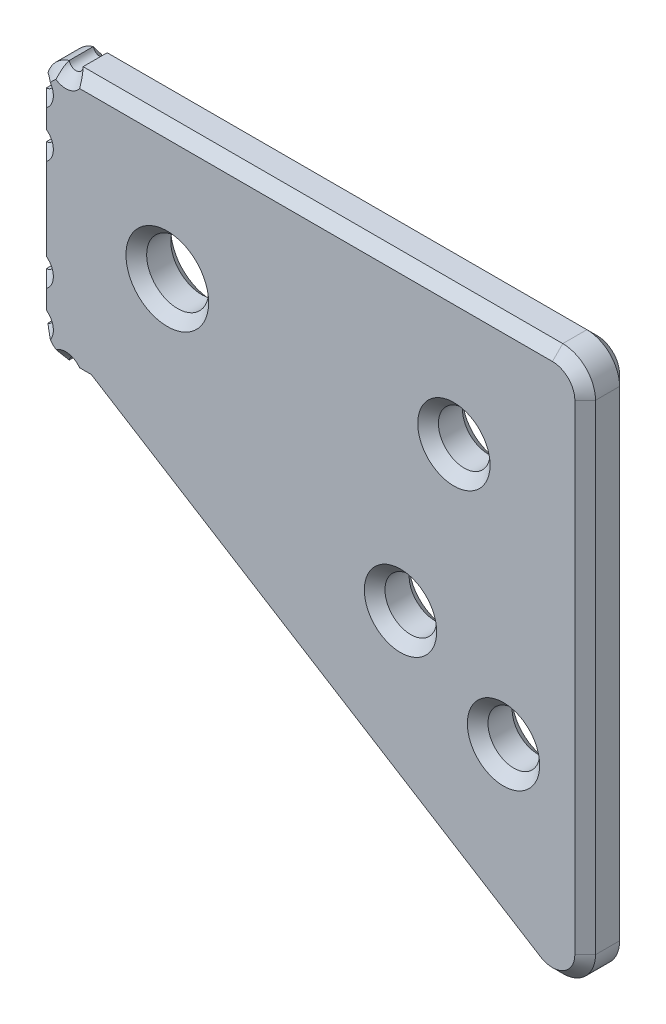
SolidWorks part; units mm, degrees
ref_plane "Front Plane" through (0, 0, 0) normal (0, 0, 1) x (1, 0, 0)
ref_plane "Top Plane" through (0, 0, 0) normal (0, 1, 0) x (1, 0, 0)
ref_plane "Right Plane" through (0, 0, 0) normal (1, 0, 0) x (0, 0, -1)
sketch "Sketch1" plane through (0, 0, 0) normal (0, 0, 1) x (1, 0, 0)
  line L3 (435.95, -297.537) -> (-11.4581, -19.05) construction
  line L9 (53.3811, -59.4088) -> (-11.4581, -19.05)
  line L11 (19.05, 19.05) -> (-13.7235, 19.05)
  line L12 (-19.05, -5.7912) -> (-19.05, 5.7912)
  line L13 (60.6412, -19.05) -> (60.6412, 14.3)
  line L14 (60.6412, -19.05) -> (60.6412, -55.3762)
  line L24 (19.05, 19.05) -> (19.05, 17.3228)
  line L25 (19.05, 17.3228) -> (704.05, 17.3228)
  line L26 (704.05, 17.3228) -> (704.05, 19.05)
  line L27 (704.05, 19.05) -> (19.05, 19.05)
  line L31 (55.8912, 19.05) -> (19.05, 19.05)
  line L44 (19.05, -6.9643) -> (19.05, -5.7912)
  line L45 (17.3228, -4.064) -> (16.7132, -4.064)
  line L46 (14.986, -5.7912) -> (14.986, -8.9963)
  line L47 (12.7826, -9.909) -> (7.8889, -5.0152)
  line L48 (6.985, -2.833) -> (6.985, 2.833)
  line L49 (7.8889, 5.0152) -> (12.7826, 9.909)
  line L50 (14.986, 8.9963) -> (14.986, 5.7912)
  line L51 (16.7132, 4.064) -> (17.3228, 4.064)
  line L52 (19.05, 5.7912) -> (19.05, 6.9643)
  line L53 (19.05, 8.9963) -> (19.05, 13.7235)
  line L54 (13.7235, 19.05) -> (8.9963, 19.05)
  line L55 (6.9643, 19.05) -> (5.7912, 19.05)
  line L56 (4.064, 17.3228) -> (4.064, 16.7132)
  line L57 (5.7912, 14.986) -> (8.9963, 14.986)
  line L58 (9.909, 12.7826) -> (5.0152, 7.8889)
  line L59 (2.833, 6.985) -> (-2.833, 6.985)
  line L60 (-5.0152, 7.8889) -> (-9.909, 12.7826)
  line L61 (-8.9963, 14.986) -> (-5.7912, 14.986)
  line L62 (-4.064, 16.7132) -> (-4.064, 17.3228)
  line L63 (-5.7912, 19.05) -> (-6.9643, 19.05)
  line L64 (-8.9963, 19.05) -> (-13.7235, 19.05)
  line L65 (-19.05, 13.7235) -> (-19.05, 8.9963)
  line L66 (-19.05, 6.9643) -> (-19.05, 5.7912)
  line L67 (-17.3228, 4.064) -> (-16.7132, 4.064)
  line L68 (-14.986, 5.7912) -> (-14.986, 8.9963)
  line L69 (-12.7826, 9.909) -> (-7.8889, 5.0152)
  line L70 (-6.985, 2.833) -> (-6.985, -2.833)
  line L71 (-7.8889, -5.0152) -> (-12.7826, -9.909)
  line L72 (-14.986, -8.9963) -> (-14.986, -5.7912)
  line L73 (-16.7132, -4.064) -> (-17.3228, -4.064)
  line L74 (-19.05, -5.7912) -> (-19.05, -6.9643)
  line L75 (-19.05, -8.9963) -> (-19.05, -13.7235)
  line L76 (-13.7235, -19.05) -> (-8.9963, -19.05)
  line L77 (-6.9643, -19.05) -> (-5.7912, -19.05)
  line L78 (-4.064, -17.3228) -> (-4.064, -16.7132)
  line L79 (-5.7912, -14.986) -> (-8.9963, -14.986)
  line L80 (-9.909, -12.7826) -> (-5.0152, -7.8889)
  line L81 (-2.833, -6.985) -> (2.833, -6.985)
  line L82 (5.0152, -7.8889) -> (9.909, -12.7826)
  line L83 (8.9963, -14.986) -> (5.7912, -14.986)
  line L84 (4.064, -16.7132) -> (4.064, -17.3228)
  line L85 (5.7912, -19.05) -> (6.9643, -19.05)
  line L86 (8.9963, -19.05) -> (13.7235, -19.05)
  line L87 (19.05, -13.7235) -> (19.05, -8.9963)
  line L108 (-8.9963, 19.05) -> (-13.7235, 19.05)
  line L109 (-19.05, 13.7235) -> (-19.05, 8.9963)
  line L110 (-19.05, 6.9643) -> (-19.05, 5.7912)
  line L118 (-19.05, -5.7912) -> (-19.05, -6.9643)
  line L119 (-19.05, -8.9963) -> (-19.05, -13.7235)
  line L120 (-13.7235, -19.05) -> (-11.4581, -19.05)
  circle A2 centre (48.7894, -34.1119) radius 3.75
  circle A3 centre (33.8406, -24.807) radius 3.75
  circle A4 centre (41.5912, 0) radius 3.75
  arc A5 (55.8912, 19.05) -> (60.6412, 14.3) centre (55.8912, 14.3) cw
  arc A6 (60.6412, -55.3762) -> (53.3811, -59.4088) centre (55.8912, -55.3762) cw
  circle A7 centre (0, 0) radius 4.5
  arc A52 (19.05, -6.9643) -> (19.05, -8.9963) centre (19.05, -7.9803) ccw
  arc A53 (19.05, -5.7912) -> (17.3228, -4.064) centre (17.3228, -5.7912) ccw
  arc A54 (16.7132, -4.064) -> (14.986, -5.7912) centre (16.7132, -5.7912) ccw
  arc A55 (12.7826, -9.909) -> (14.986, -8.9963) centre (13.6953, -8.9963) ccw
  arc A56 (6.985, -2.833) -> (7.8889, -5.0152) centre (10.0711, -2.833) ccw
  arc A57 (7.8889, 5.0152) -> (6.985, 2.833) centre (10.0711, 2.833) ccw
  arc A58 (14.986, 8.9963) -> (12.7826, 9.909) centre (13.6953, 8.9963) ccw
  arc A59 (14.986, 5.7912) -> (16.7132, 4.064) centre (16.7132, 5.7912) ccw
  arc A60 (17.3228, 4.064) -> (19.05, 5.7912) centre (17.3228, 5.7912) ccw
  arc A61 (19.05, 8.9963) -> (19.05, 6.9643) centre (19.05, 7.9803) ccw
  arc A62 (18.8293, 15.7312) -> (19.05, 13.7235) centre (19.05, 14.7395) ccw
  arc A63 (18.8293, 15.7312) -> (15.7312, 18.8293) centre (14.3002, 14.3002) ccw
  arc A64 (13.7235, 19.05) -> (15.7312, 18.8293) centre (14.7395, 19.05) ccw
  arc A65 (6.9643, 19.05) -> (8.9963, 19.05) centre (7.9803, 19.05) ccw
  arc A66 (5.7912, 19.05) -> (4.064, 17.3228) centre (5.7912, 17.3228) ccw
  arc A67 (4.064, 16.7132) -> (5.7912, 14.986) centre (5.7912, 16.7132) ccw
  arc A68 (9.909, 12.7826) -> (8.9963, 14.986) centre (8.9963, 13.6953) ccw
  arc A69 (2.833, 6.985) -> (5.0152, 7.8889) centre (2.833, 10.0711) ccw
  arc A70 (-5.0152, 7.8889) -> (-2.833, 6.985) centre (-2.833, 10.0711) ccw
  arc A71 (-8.9963, 14.986) -> (-9.909, 12.7826) centre (-8.9963, 13.6953) ccw
  arc A72 (-5.7912, 14.986) -> (-4.064, 16.7132) centre (-5.7912, 16.7132) ccw
  arc A73 (-4.064, 17.3228) -> (-5.7912, 19.05) centre (-5.7912, 17.3228) ccw
  arc A74 (-8.9963, 19.05) -> (-6.9643, 19.05) centre (-7.9803, 19.05) ccw
  arc A75 (-15.7312, 18.8293) -> (-13.7235, 19.05) centre (-14.7395, 19.05) ccw
  arc A76 (-15.7312, 18.8293) -> (-18.8293, 15.7312) centre (-14.3002, 14.3002) ccw
  arc A77 (-19.05, 13.7235) -> (-18.8293, 15.7312) centre (-19.05, 14.7395) ccw
  arc A78 (-19.05, 6.9643) -> (-19.05, 8.9963) centre (-19.05, 7.9803) ccw
  arc A79 (-19.05, 5.7912) -> (-17.3228, 4.064) centre (-17.3228, 5.7912) ccw
  arc A80 (-16.7132, 4.064) -> (-14.986, 5.7912) centre (-16.7132, 5.7912) ccw
  arc A81 (-12.7826, 9.909) -> (-14.986, 8.9963) centre (-13.6953, 8.9963) ccw
  arc A82 (-6.985, 2.833) -> (-7.8889, 5.0152) centre (-10.0711, 2.833) ccw
  arc A83 (-7.8889, -5.0152) -> (-6.985, -2.833) centre (-10.0711, -2.833) ccw
  arc A84 (-14.986, -8.9963) -> (-12.7826, -9.909) centre (-13.6953, -8.9963) ccw
  arc A85 (-14.986, -5.7912) -> (-16.7132, -4.064) centre (-16.7132, -5.7912) ccw
  arc A86 (-17.3228, -4.064) -> (-19.05, -5.7912) centre (-17.3228, -5.7912) ccw
  arc A87 (-19.05, -8.9963) -> (-19.05, -6.9643) centre (-19.05, -7.9803) ccw
  arc A88 (-18.8293, -15.7312) -> (-19.05, -13.7235) centre (-19.05, -14.7395) ccw
  arc A89 (-18.8293, -15.7312) -> (-15.7312, -18.8293) centre (-14.3002, -14.3002) ccw
  arc A90 (-13.7235, -19.05) -> (-15.7312, -18.8293) centre (-14.7395, -19.05) ccw
  arc A91 (-6.9643, -19.05) -> (-8.9963, -19.05) centre (-7.9803, -19.05) ccw
  arc A92 (-5.7912, -19.05) -> (-4.064, -17.3228) centre (-5.7912, -17.3228) ccw
  arc A93 (-4.064, -16.7132) -> (-5.7912, -14.986) centre (-5.7912, -16.7132) ccw
  arc A94 (-9.909, -12.7826) -> (-8.9963, -14.986) centre (-8.9963, -13.6953) ccw
  arc A95 (-2.833, -6.985) -> (-5.0152, -7.8889) centre (-2.833, -10.0711) ccw
  arc A96 (5.0152, -7.8889) -> (2.833, -6.985) centre (2.833, -10.0711) ccw
  arc A97 (8.9963, -14.986) -> (9.909, -12.7826) centre (8.9963, -13.6953) ccw
  arc A98 (5.7912, -14.986) -> (4.064, -16.7132) centre (5.7912, -16.7132) ccw
  arc A99 (4.064, -17.3228) -> (5.7912, -19.05) centre (5.7912, -17.3228) ccw
  arc A100 (8.9963, -19.05) -> (6.9643, -19.05) centre (7.9803, -19.05) ccw
  arc A101 (15.7312, -18.8293) -> (13.7235, -19.05) centre (14.7395, -19.05) ccw
  arc A102 (15.7312, -18.8293) -> (18.8293, -15.7312) centre (14.3002, -14.3002) ccw
  arc A103 (19.05, -13.7235) -> (18.8293, -15.7312) centre (19.05, -14.7395) ccw
  arc A127 (-15.7312, 18.8293) -> (-13.7235, 19.05) centre (-14.7395, 19.05) ccw
  arc A128 (-15.7312, 18.8293) -> (-18.8293, 15.7312) centre (-14.3002, 14.3002) ccw
  arc A129 (-19.05, 13.7235) -> (-18.8293, 15.7312) centre (-19.05, 14.7395) ccw
  arc A130 (-19.05, 6.9643) -> (-19.05, 8.9963) centre (-19.05, 7.9803) ccw
  arc A139 (-19.05, -8.9963) -> (-19.05, -6.9643) centre (-19.05, -7.9803) ccw
  arc A140 (-18.8293, -15.7312) -> (-19.05, -13.7235) centre (-19.05, -14.7395) ccw
  arc A141 (-18.8293, -15.7312) -> (-15.7312, -18.8293) centre (-14.3002, -14.3002) ccw
  arc A142 (-13.7235, -19.05) -> (-15.7312, -18.8293) centre (-14.7395, -19.05) ccw
  dimension "D4" = 4.75
  dimension "D1" = 0
  dimension "D3" = 0
extrude "Boss-Extrude1" add sketch "Sketch1" along normal blind 6.5
chamfer "Chamfer1" distance 1.5 angle 45 42 edges at (52.5394, -34.1119, 0) (37.5906, -24.807, 0) (45.3412, 0, 0) (-12.5908, -19.05, 0) (20.9615, -39.2294, 0) (58.1976, -59.5286, 0) (60.6412, -20.5381, 0) (59.2499, 17.6588, 0) (21.0838, 19.05, 0) (-14.6285, 18.0401, 0) (-17.6588, 17.6588, 0) (-18.0401, 14.6285, 0) (-19.05, 11.3599, 0) (-18.034, 7.9803, 0) (-19.05, 0, 0) (-18.034, -7.9803, 0) (-19.05, -11.3599, 0) (-18.0401, -14.6285, 0) (-17.6588, -17.6588, 0) (-14.6285, -18.0401, 0) (52.5394, -34.1119, 6.5) (37.5906, -24.807, 6.5) (45.3412, 0, 6.5) (-17.6588, -17.6588, 6.5) (-18.0401, -14.6285, 6.5) (-19.05, -11.3599, 6.5) (-18.034, -7.9803, 6.5) (-19.05, 0, 6.5) (-18.034, 7.9803, 6.5) (-19.05, 11.3599, 6.5) (-18.0401, 14.6285, 6.5) (-17.6588, 17.6588, 6.5) (-14.6285, 18.0401, 6.5) (21.0838, 19.05, 6.5) (59.2499, 17.6588, 6.5) (60.6412, -20.5381, 6.5) (58.1976, -59.5286, 6.5) (20.9615, -39.2294, 6.5) (-12.5908, -19.05, 6.5) (-14.6285, -18.0401, 6.5) (4.5, 0, 0) (4.5, 0, 6.5)
